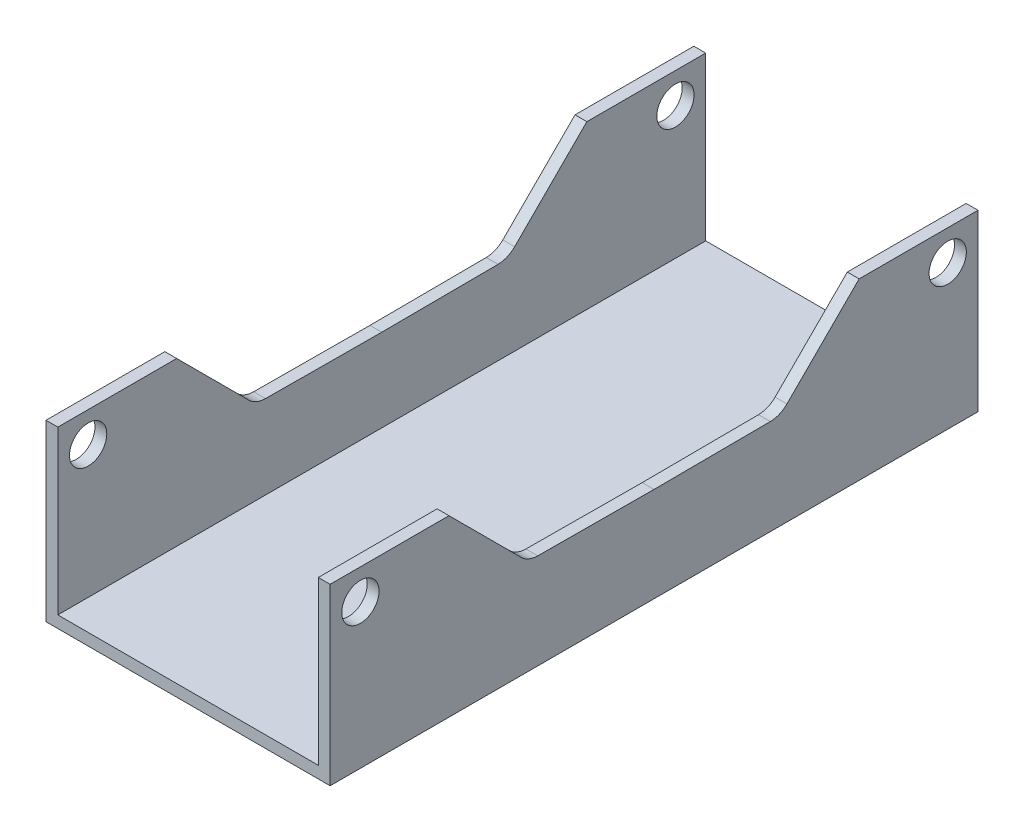
SolidWorks part; units mm, degrees
material "AISI 1020"
ref_plane "Front Plane" through (0, 0, 0) normal (0, 0, 1) x (1, 0, 0)
ref_plane "Top Plane" through (0, 0, 0) normal (0, 1, 0) x (1, 0, 0)
ref_plane "Right Plane" through (0, 0, 0) normal (1, 0, 0) x (0, 0, -1)
sketch "Sketch1" plane through (0, 0, 0) normal (0, 0, 1) x (1, 0, 0)
  line L0 (-34.925, 22.225) -> (34.925, 22.225)
  line L1 (-38.1, -25.4) -> (38.1, -25.4)
  line L2 (-38.1, -25.4) -> (-38.1, 25.4)
  line L3 (-38.1, 25.4) -> (38.1, 25.4)
  line L4 (38.1, -25.4) -> (38.1, 25.4)
  line L5 (-38.1, -25.4) -> (38.1, 25.4) construction
  line L6 (-38.1, 25.4) -> (38.1, -25.4) construction
  line L7 (34.925, -22.225) -> (34.925, 22.225)
  line L8 (-34.925, -22.225) -> (34.925, -22.225)
  line L9 (-34.925, -22.225) -> (-34.925, 22.225)
  point P0 (0, 0)
  dimension "D1" = 76.2
  dimension "D2" = 50.8
  dimension "D3" = 3.175
extrude "Boss-Extrude1" add sketch "Sketch1" along normal blind 173.75
sketch "Sketch2" plane through (0, 0, 0) normal (1, 0, 0) x (0, 0, -1)
  line L0 (0, -25.4) -> (0, 25.4) construction
  line L1 (-173.75, 25.4) -> (0, 25.4)
  line L2 (-173.75, 25.4) -> (-173.75, 21.4)
  line L3 (-173.75, 21.4) -> (-141.875, 21.4)
  line L4 (0, 25.4) -> (0, 21.4)
  line L5 (-173.75, 21.4) -> (-165.625, 21.4) construction
  line L6 (-165.625, 21.4) -> (-165.625, 13.275) construction
  line L7 (-86.875, 21.4) -> (-86.875, -25.4) construction
  line L8 (-173.75, -25.4) -> (0, -25.4) construction
  line L9 (-120.6618, 0.1868) -> (-86.875, 0)
  line L10 (-141.875, 21.4) -> (-120.6618, 0.1868)
  line L11 (-31.875, 21.4) -> (-53.0882, 0.1868)
  line L12 (-53.0882, 0.1868) -> (-86.875, 0)
  line L14 (-31.875, 21.4) -> (0, 21.4)
  line L15 (-86.875, 21.4) -> (-141.875, 21.4) construction
  circle A1 centre (-165.625, 13.275) radius 5
  circle A2 centre (-8.125, 13.275) radius 5
  point P22 (-86.875, 0)
  dimension "D2" = 55
  dimension "D5" = 10
  dimension "D1" = 4
  dimension "D3" = 8.125
  dimension "D4" = 8.125
  dimension "D6" = 45
  dimension "D7" = 30
extrude "Cut-Extrude1" cut sketch "Sketch2" against normal through all both and the other way through all
fillet "Fillet1" radius 6.35 4 edges at (-36.5125, 0.1868, 53.0882) (36.5125, 0.1868, 53.0882) (36.5125, 0.1868, 120.6618) (-36.5125, 0.1868, 120.6618)
